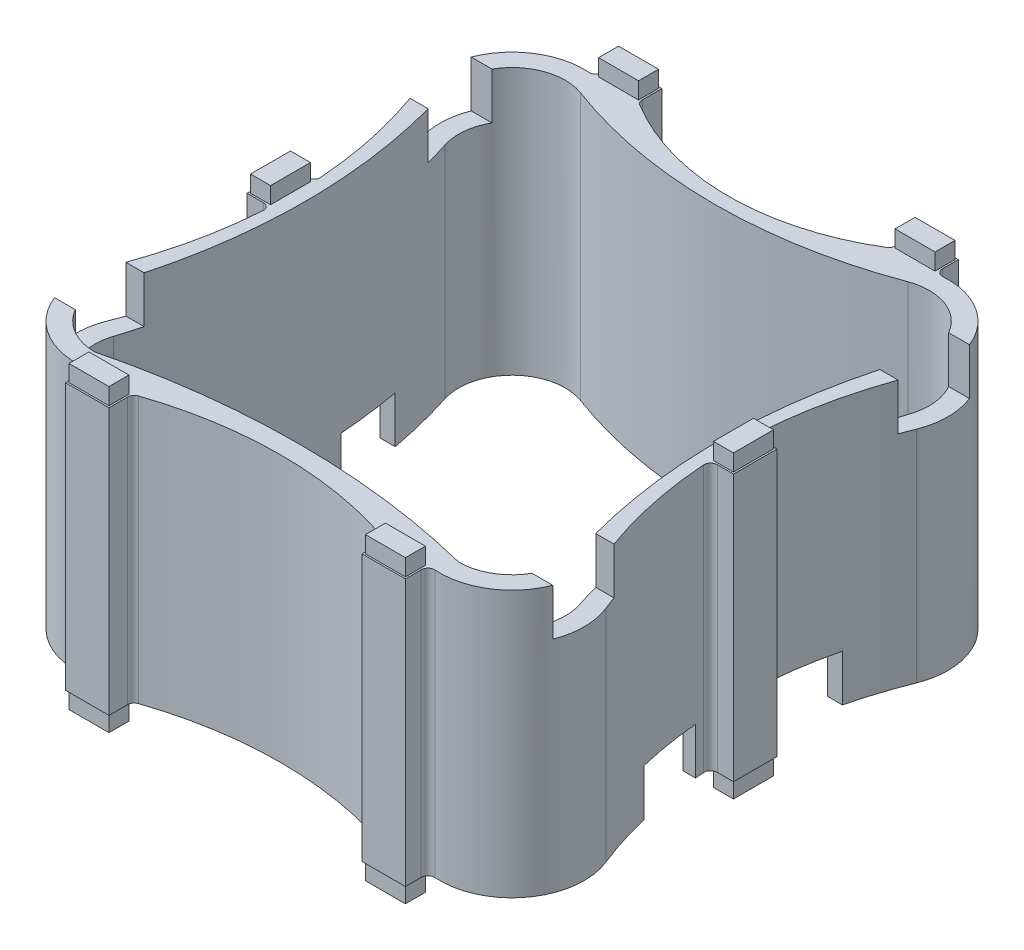
SolidWorks part; units mm, degrees
material "尼龙 101"
ref_plane "前视基准面" through (0, 0, 0) normal (0, 0, 1) x (1, 0, 0)
ref_plane "上视基准面" through (0, 0, 0) normal (0, 1, 0) x (1, 0, 0)
ref_plane "右视基准面" through (0, 0, 0) normal (1, 0, 0) x (0, 0, -1)
sketch "参考面" plane through (0, 0, 0) normal (0, 1, 0) x (1, 0, 0)
  line L9 (-126.3139, 0) -> (116.7252, 0) construction
  line L10 (121.4406, 121.4406) -> (-121.4406, -121.4406) construction
  line L19 (-81.1154, 0) -> (102.0168, 0) construction
  line L20 (-108.2303, 108.2303) -> (124.7404, -124.7404) construction
  line L37 (0, 0) -> (86.2111, -62.636) construction
  line L56 (0, 63.4476) -> (0, -83.7805) construction
  line L92 (67.1165, -56.1685) -> (56.6027, -48.5298)
  line L94 (74.1596, -46.4745) -> (63.6458, -38.8359)
  line L111 (14.4084, 23.7665) -> (0, 9.3581)
  line L112 (21.4, 67.209) -> (28.6, 67.209)
  line L121 (4.0949, -56.1675) -> (4.0949, -53.2193)
  line L122 (-3.5956, -56.6668) -> (3.5956, -56.6668)
  line L123 (3.5956, -40.6902) -> (-3.5938, -40.6902)
  line L124 (4.0949, -41.1895) -> (4.0949, -44.1377)
  line L125 (-4.0949, -56.1675) -> (-4.0949, -53.2179)
  line L126 (-4.0949, -44.1363) -> (-4.0949, -41.1876)
  line L127 (-4.5418, -52.8684) -> (-4.4444, -52.8684)
  line L128 (-8.5359, -48.8743) -> (-8.5359, -48.4799)
  line L129 (8.5359, -48.8757) -> (8.5359, -48.4813)
  line L130 (4.4444, -52.8698) -> (4.5418, -52.8698)
  line L131 (4.5418, -44.4872) -> (4.4444, -44.4872)
  line L132 (-4.5418, -44.4858) -> (-4.4444, -44.4858)
  line L180 (-67.1165, 56.1685) -> (-56.6027, 48.5298)
  line L181 (-74.1596, 46.4745) -> (-63.6458, 38.8359)
  line L182 (-74.1596, -46.4745) -> (-63.6458, -38.8359)
  line L183 (-67.1165, -56.1685) -> (-56.6027, -48.5298)
  line L194 (-18.9731, -62.4083) -> (18.9712, -62.4083) construction
  line L200 (-11.2634, 52.145) -> (-6.2707, 52.145) construction
  line L201 (-11.2634, 50.8469) -> (-6.2707, 50.8469)
  line L202 (-11.2634, 53.4431) -> (-6.2707, 53.4431)
  line L206 (5.7117, 52.145) -> (0.719, 52.145) construction
  line L207 (5.7117, 53.4431) -> (0.719, 53.4431)
  line L208 (5.7117, 50.8469) -> (0.719, 50.8469)
  line L209 (74.1596, 46.4745) -> (63.6458, 38.8359)
  line L210 (43.9796, 31.9531) -> (60.1362, 43.6915) construction
  line L211 (67.1165, 56.1685) -> (56.6027, 48.5298)
  line L213 (-23.7665, 14.4084) -> (-9.3581, 0)
  line L214 (-58.8004, 0) -> (57.5251, 0) construction
  line L215 (-23.7665, -14.4084) -> (-9.3581, 0)
  line L241 (20.9, 49.291) -> (20.9, 66.709)
  line L242 (21.4, 48.791) -> (28.6, 48.791)
  line L243 (-14.4084, 23.7665) -> (0, 9.3581)
  line L244 (20.9, 58) -> (35.2287, 58) construction
  line L245 (25, 67.209) -> (25, 48.791) construction
  line L246 (29.1, 66.709) -> (29.1, 49.291)
  line L247 (23.7665, -14.4084) -> (9.3581, 0)
  line L248 (23.7665, 14.4084) -> (9.3581, 0)
  line L249 (-14.4084, -23.7665) -> (0, -9.3581)
  line L250 (14.4084, -23.7665) -> (0, -9.3581)
  line L255 (25.5, -41.5) -> (19, -41.5)
  line L256 (-25.5, 41.5) -> (-19, 41.5)
  line L257 (-25.5, 41.5) -> (-25.5, 38)
  line L258 (-25.5, 38) -> (-19, 38)
  line L259 (-19, 41.5) -> (-19, 38)
  line L260 (-36.5, 3.25) -> (-33, 3.25)
  line L261 (-36.5, 3.25) -> (-36.5, -3.25)
  line L262 (-36.5, -3.25) -> (-33, -3.25)
  line L263 (-33, 3.25) -> (-33, -3.25)
  line L264 (-25.5, -38) -> (-19, -38)
  line L265 (-25.5, -38) -> (-25.5, -41.5)
  line L266 (-25.5, -41.5) -> (-19, -41.5)
  line L267 (-19, -38) -> (-19, -41.5)
  line L268 (19, -38) -> (19, -41.5)
  line L269 (25.5, -38) -> (19, -38)
  line L270 (25.5, -38) -> (25.5, -41.5)
  line L271 (36.5, -3.25) -> (33, -3.25)
  line L272 (33, 3.25) -> (33, -3.25)
  line L273 (36.5, 3.25) -> (33, 3.25)
  line L274 (36.5, 3.25) -> (36.5, -3.25)
  line L275 (25.5, 38) -> (19, 38)
  line L276 (19, 41.5) -> (19, 38)
  line L277 (25.5, 41.5) -> (25.5, 38)
  line L278 (25.5, 41.5) -> (19, 41.5)
  circle A40 centre (9.9853, 9.9853) radius 1.0734
  circle A65 centre (12.7313, 12.7313) radius 1.0734
  circle A66 centre (15.2276, 15.2276) radius 1.5477
  circle A67 centre (-15.2276, 15.2276) radius 1.5477
  circle A68 centre (-12.7313, 12.7313) radius 1.0734
  circle A69 centre (-9.9853, 9.9853) radius 1.0734
  circle A70 centre (-9.9853, -9.9853) radius 1.0734
  circle A71 centre (-12.7313, -12.7313) radius 1.0734
  circle A72 centre (-15.2276, -15.2276) radius 1.5477
  circle A82 centre (15.2276, -15.2276) radius 1.5477
  circle A83 centre (12.7313, -12.7313) radius 1.0734
  circle A84 centre (9.9853, -9.9853) radius 1.0734
  circle A85 centre (27.9589, -27.9589) radius 3.1454
  circle A86 centre (-27.9589, -27.9589) radius 3.1454
  circle A101 centre (-27.9589, 27.9589) radius 3.1454
  circle A102 centre (27.9589, 27.9589) radius 3.1454
  circle A104 centre (43.9796, -31.9531) radius 1.5477
  circle A105 centre (60.1362, -43.6915) radius 1.5477
  circle A106 centre (-60.1362, -43.6915) radius 1.5477
  circle A113 centre (-23.2458, 52.145) radius 1.2981
  circle A114 centre (-43.9796, -31.9531) radius 1.5477
  circle A115 centre (60.1362, 43.6915) radius 1.5477
  circle A116 centre (43.9796, 31.9531) radius 1.5477
  circle A117 centre (-43.9796, 31.9531) radius 1.5477
  circle A118 centre (-60.1362, 43.6915) radius 1.5477
  arc A120 (67.1165, -56.1685) -> (74.1596, -46.4745) centre (70.638, -51.3215) ccw
  arc A121 (27.2174, -63.5024) -> (56.6027, -48.5298) centre (45.7245, -63.5024) cw
  arc A128 (-4.0949, -56.1675) -> (-3.5956, -56.6668) centre (-4.0949, -56.6668) ccw
  arc A129 (4.0949, -56.1675) -> (3.5956, -56.6668) centre (4.0949, -56.6668) cw
  arc A130 (4.0949, -41.1895) -> (3.5956, -40.6902) centre (4.0949, -40.6902) ccw
  arc A131 (-4.0949, -41.1876) -> (-3.5938, -40.6902) centre (-4.0931, -40.6884) cw
  arc A132 (8.5359, -48.4813) -> (4.5418, -44.4872) centre (4.5418, -48.4813) ccw
  arc A133 (-4.5418, -44.4858) -> (-8.5359, -48.4799) centre (-4.5418, -48.4799) ccw
  arc A134 (-4.5418, -52.8684) -> (-8.5359, -48.8743) centre (-4.5418, -48.8743) cw
  arc A135 (8.5359, -48.8757) -> (4.5418, -52.8698) centre (4.5418, -48.8757) cw
  arc A136 (4.0949, -44.1377) -> (4.4444, -44.4872) centre (4.4444, -44.1377) ccw
  arc A137 (4.0949, -53.2193) -> (4.4444, -52.8698) centre (4.4444, -53.2193) cw
  arc A138 (-4.0949, -44.1363) -> (-4.4444, -44.4858) centre (-4.4444, -44.1363) cw
  arc A139 (-4.0949, -53.2179) -> (-4.4444, -52.8684) centre (-4.4444, -53.2179) ccw
  arc A165 (-11.2634, 50.8469) -> (-11.2634, 53.4431) centre (-11.2634, 52.145) cw
  arc A166 (-6.2707, 53.4431) -> (-6.2707, 50.8469) centre (-6.2707, 52.145) cw
  arc A169 (5.7117, 53.4431) -> (5.7117, 50.8469) centre (5.7117, 52.145) cw
  arc A170 (0.719, 50.8469) -> (0.719, 53.4431) centre (0.719, 52.145) cw
  circle A175 centre (0, -38.4435) radius 1.5477
  circle A176 centre (0, -58.9135) radius 1.5477
  arc A177 (67.1165, 56.1685) -> (74.1596, 46.4745) centre (70.638, 51.3215) cw
  arc A178 (63.6458, 38.8359) -> (63.6458, -38.8359) centre (91.8617, 0) ccw
  circle A179 centre (43.9796, -31.9531) radius 5.9912 construction
  arc A180 (35.3497, 58.9683) -> (56.6027, 48.5298) centre (48.7329, 59.3617) ccw
  arc A181 (-67.1165, 56.1685) -> (-74.1596, 46.4745) centre (-70.638, 51.3215) ccw
  arc A182 (-35.3497, 58.9683) -> (-56.6027, 48.5298) centre (-48.7329, 59.3617) cw
  arc A183 (-63.6458, 38.8359) -> (-63.6458, -38.8359) centre (-91.8617, 0) cw
  arc A184 (-67.1165, -56.1685) -> (-74.1596, -46.4745) centre (-70.638, -51.3215) cw
  arc A185 (-27.2174, -63.5024) -> (-56.6027, -48.5298) centre (-45.7245, -63.5024) ccw
  arc A190 (-23.7665, 14.4084) -> (-29.7764, 19.3723) centre (-52.8107, -14.6358) ccw
  arc A191 (-23.7665, -14.4084) -> (-29.7764, -19.3723) centre (-52.8107, 14.6358) cw
  arc A192 (-29.7764, -19.3723) -> (-29.7764, 19.3723) centre (-91.8617, 0) ccw
  circle A202 centre (25, 69.659) radius 1.05
  arc A203 (20.9, 66.709) -> (21.4, 67.209) centre (20.9, 67.209) cw
  arc A204 (20.9, 49.291) -> (21.4, 48.791) centre (20.9, 48.791) ccw
  circle A205 centre (25, 46.341) radius 1.05
  arc A206 (29.1, 66.709) -> (28.6, 67.209) centre (29.1, 67.209) ccw
  arc A207 (29.1, 49.291) -> (28.6, 48.791) centre (29.1, 48.791) cw
  arc A208 (-14.4084, 23.7665) -> (-19.3723, 29.7764) centre (14.6358, 52.8107) cw
  arc A209 (-19.3723, 29.7764) -> (19.3723, 29.7764) centre (0, 91.8617) ccw
  arc A210 (14.4084, 23.7665) -> (19.3723, 29.7764) centre (-14.6358, 52.8107) ccw
  arc A211 (23.7665, 14.4084) -> (29.7764, 19.3723) centre (52.8107, -14.6358) cw
  arc A212 (29.7764, 19.3723) -> (29.7764, -19.3723) centre (91.8617, 0) ccw
  arc A213 (23.7665, -14.4084) -> (29.7764, -19.3723) centre (52.8107, 14.6358) ccw
  arc A214 (14.4084, -23.7665) -> (19.3723, -29.7764) centre (-14.6358, -52.8107) cw
  arc A215 (19.3723, -29.7764) -> (-19.3723, -29.7764) centre (0, -91.8617) ccw
  arc A216 (-14.4084, -23.7665) -> (-19.3723, -29.7764) centre (14.6358, -52.8107) ccw
  point P77 (0, 0)
  point P112 (-8.7671, 52.145)
  point P168 (3.2153, 52.145)
  point P443 (0, 0)
  dimension "D1" = 4
  dimension "D3" = 58
  dimension "D5" = 8.2
  dimension "D2" = 0.5
  dimension "D4" = 2.45
  dimension "D6" = 7.2
  dimension "D7" = 25
  dimension "D8" = 19
  dimension "D9" = 33
  dimension "D14" = 6.5
  dimension "D15" = 3.5
  dimension "D16" = 38
  dimension "D17" = 38
sketch "草图2" plane through (0, 0, 0) normal (0, 1, 0) x (1, 0, 0)
  line L1 (-61.3007, 0) -> (77.257, 0) construction
  line L8 (-33, 3.25) -> (-36.5, 3.25)
  line L9 (-36.5, 3.25) -> (-36.5, -3.25)
  line L31 (-36.5, -3.25) -> (-33, -3.25)
  line L33 (-25.5, 38) -> (-25.5, 41.5)
  line L56 (-25.5, 41.5) -> (-19, 41.5)
  line L57 (-19, 41.5) -> (-19, 38)
  line L58 (-25.5, -38) -> (-25.5, -41.5)
  line L59 (-25.5, -41.5) -> (-19, -41.5)
  line L60 (-19, -41.5) -> (-19, -38)
  line L61 (19, -41.5) -> (19, -38)
  line L62 (25.5, -41.5) -> (19, -41.5)
  line L63 (25.5, -38) -> (25.5, -41.5)
  line L64 (19, 41.5) -> (19, 38)
  line L65 (25.5, 41.5) -> (19, 41.5)
  line L66 (25.5, 38) -> (25.5, 41.5)
  line L67 (36.5, -3.25) -> (33, -3.25)
  line L68 (36.5, 3.25) -> (36.5, -3.25)
  line L69 (33, 3.25) -> (36.5, 3.25)
  line L74 (-126.3139, 0) -> (116.7252, 0) construction
  line L75 (0, 68.5797) -> (0, -68.5797) construction
  line L76 (0, 63.4476) -> (0, -83.7805) construction
  line L77 (-108.2303, 108.2303) -> (124.7404, -124.7404) construction
  arc A49 (-25.5, 38) -> (-37.3844, 23.3059) centre (-27.3145, 27.3145) ccw
  arc A52 (-24.5842, 34.8413) -> (-34.9442, 24.8864) centre (-27.3145, 27.3145) ccw
  arc A53 (-34.9442, -24.8864) -> (-34.9442, 24.8864) centre (-113.1442, 0) ccw
  arc A55 (-37.3844, -23.3059) -> (-33, -3.25) centre (-95.9302, 0) ccw
  arc A56 (-25.5, -38) -> (-37.3844, -23.3059) centre (-27.3145, -27.3145) cw
  arc A57 (-27.3357, -35.3212) -> (-34.9442, -24.8864) centre (-27.3145, -27.3145) cw
  arc A59 (-33, 3.25) -> (-37.3844, 23.3059) centre (-95.9302, 0) ccw
  arc A62 (33, 3.25) -> (37.3844, 23.3059) centre (95.9302, 0) cw
  arc A65 (27.3357, -35.3212) -> (34.9442, -24.8864) centre (27.3145, -27.3145) ccw
  arc A66 (25.5, -38) -> (37.3844, -23.3059) centre (27.3145, -27.3145) ccw
  arc A69 (37.3844, -23.3059) -> (33, -3.25) centre (95.9302, 0) cw
  arc A70 (34.9442, -24.8864) -> (34.9442, 24.8864) centre (113.1442, 0) cw
  arc A71 (24.5842, 34.8413) -> (34.9442, 24.8864) centre (27.3145, 27.3145) cw
  arc A72 (25.5, 38) -> (37.3844, 23.3059) centre (27.3145, 27.3145) cw
  arc A73 (-19, 38) -> (19, 38) centre (0, 67.9818) ccw
  arc A74 (-24.5842, 34.8413) -> (24.5842, 34.8413) centre (0, 100.6181) ccw
  arc A75 (-19, -38) -> (19, -38) centre (0, -91.6977) cw
  arc A76 (-27.3357, -35.3212) -> (27.3357, -35.3212) centre (0, -143.9681) cw
extrude "凸台-拉伸1" add sketch "草图2" against normal blind 40
sketch "草图5" plane through (0, 0, 0) normal (0, 1, 0) x (1, 0, 0)
  line L0 (-68.648, 0) -> (77.219, 0) construction
  line L1 (-126.3139, 0) -> (116.7252, 0) construction
  line L2 (0, 57.3258) -> (0, -69.9488) construction
  line L3 (0, 63.4476) -> (0, -83.7805) construction
  line L4 (-36.5, 3.25) -> (-33, 3.25) construction
  line L5 (-36.25, 3) -> (-33.25, 3)
  line L6 (-36.25, 3) -> (-36.25, -3)
  line L7 (-36.25, -3) -> (-33.25, -3)
  line L8 (-33.25, 3) -> (-33.25, -3)
  line L9 (-36.5, 3.25) -> (-36.5, -3.25) construction
  line L10 (-19, -38) -> (-19, -41.5) construction
  line L11 (-25.25, -38.25) -> (-19.25, -38.25)
  line L12 (-25.25, -38.25) -> (-25.25, -41.25)
  line L13 (-25.25, -41.25) -> (-19.25, -41.25)
  line L14 (-19.25, -38.25) -> (-19.25, -41.25)
  line L15 (-25.5, -41.5) -> (-19, -41.5) construction
  line L16 (-25.25, 41.25) -> (-19.25, 41.25)
  line L17 (-19.25, 38.25) -> (-19.25, 41.25)
  line L18 (-25.25, 38.25) -> (-19.25, 38.25)
  line L19 (-25.25, 38.25) -> (-25.25, 41.25)
  line L20 (25.25, 38.25) -> (25.25, 41.25)
  line L21 (25.25, 38.25) -> (19.25, 38.25)
  line L22 (19.25, 38.25) -> (19.25, 41.25)
  line L23 (25.25, 41.25) -> (19.25, 41.25)
  line L24 (19.25, -38.25) -> (19.25, -41.25)
  line L25 (25.25, -41.25) -> (19.25, -41.25)
  line L26 (25.25, -38.25) -> (25.25, -41.25)
  line L27 (25.25, -38.25) -> (19.25, -38.25)
  line L28 (33.25, 3) -> (33.25, -3)
  line L29 (36.25, -3) -> (33.25, -3)
  line L30 (36.25, 3) -> (36.25, -3)
  line L31 (36.25, 3) -> (33.25, 3)
  dimension "D1" = 0.25
  dimension "D2" = 0.25
  dimension "D3" = 3
  dimension "D4" = 0.25
  dimension "D5" = 0.25
extrude "凸台-拉伸3" add sketch "草图5" along normal blind 2.5
sketch "草图6" plane through (0, -40, 0) normal (0, -1, 0) x (1, 0, 0)
  line L0 (-44.389, 0) -> (42.3877, 0) construction
  line L1 (0, 51.2716) -> (0, -51.2716) construction
  line L2 (-25.25, 41.25) -> (-19.25, 41.25)
  line L3 (-36.25, 3) -> (-33.25, 3)
  line L4 (-36.25, 3) -> (-36.25, -3)
  line L5 (-36.25, -3) -> (-33.25, -3)
  line L6 (-33.25, 3) -> (-33.25, -3)
  line L7 (-25.25, -38.25) -> (-19.25, -38.25)
  line L8 (-25.25, -38.25) -> (-25.25, -41.25)
  line L9 (-25.25, -41.25) -> (-19.25, -41.25)
  line L10 (-19.25, -38.25) -> (-19.25, -41.25)
  line L11 (-19.25, 38.25) -> (-19.25, 41.25)
  line L12 (-25.25, 38.25) -> (-19.25, 38.25)
  line L13 (-25.25, 38.25) -> (-25.25, 41.25)
  line L14 (25.25, 38.25) -> (25.25, 41.25)
  line L15 (25.25, 38.25) -> (19.25, 38.25)
  line L16 (19.25, 38.25) -> (19.25, 41.25)
  line L17 (19.25, -38.25) -> (19.25, -41.25)
  line L18 (25.25, -41.25) -> (19.25, -41.25)
  line L19 (25.25, -38.25) -> (25.25, -41.25)
  line L20 (25.25, -38.25) -> (19.25, -38.25)
  line L21 (33.25, 3) -> (33.25, -3)
  line L22 (36.25, -3) -> (33.25, -3)
  line L23 (36.25, 3) -> (36.25, -3)
  line L24 (36.25, 3) -> (33.25, 3)
  line L25 (25.25, 41.25) -> (19.25, 41.25)
  line L26 (-36.5, 3.25) -> (-33, 3.25) construction
  line L27 (-36.5, -3.25) -> (-36.5, 3.25) construction
  line L28 (-25.5, -41.5) -> (-25.5, -38) construction
  line L29 (-19, -41.5) -> (-25.5, -41.5) construction
  dimension "D1" = 0.25
  dimension "D2" = 0.25
  dimension "D3" = 0.25
  dimension "D4" = 0.25
  dimension "D5" = 3
extrude "凸台-拉伸4" add sketch "草图6" along normal blind 2.5
fillet "圆角1" radius 1 12 edges at (33, -20, -3.25) (25.5, -20, -38) (-19, -20, -38) (19, -20, -38) (-25.5, -20, -38) (-33, -20, -3.25) (19, -20, 38) (33, -20, 3.25) (25.5, -20, 38) (-19, -20, 38) (-25.5, -20, 38) (-33, -20, 3.25)
sketch "草图7" plane through (0, 0, 0) normal (0, 1, 0) x (1, 0, 0)
  line L0 (-43.0337, 0) -> (42.851, 0) construction
  line L1 (0, 36.718) -> (0, -44.8375) construction
  line L2 (0, 0) -> (-41.2356, -29.9594) construction
  line L3 (-36.6337, -21.3237) -> (-33.8986, -21.3237)
  line L4 (-37.4219, -31.2746) -> (-34.2733, -31.2746)
  line L5 (36.6337, -21.3237) -> (33.8986, -21.3237)
  line L6 (37.4219, -31.2746) -> (34.2733, -31.2746)
  line L8 (-36.6337, 21.3237) -> (-33.8986, 21.3237)
  line L9 (-37.4219, 31.2746) -> (-34.2733, 31.2746)
  line L10 (37.4219, 31.2746) -> (34.2733, 31.2746)
  line L11 (36.6337, 21.3237) -> (33.8986, 21.3237)
  arc A0 (-34.9442, -24.8864) -> (-34.2733, -31.2746) centre (-27.2797, -27.3109) ccw
  arc A1 (-37.606, -23.8549) -> (-37.4219, -31.2746) centre (-27.2797, -27.3109) ccw
  arc A2 (-37.606, -23.8549) -> (-36.6337, -21.3237) centre (-95.9302, 0) ccw
  arc A3 (-34.9442, -24.8864) -> (-33.8986, -21.3237) centre (-113.1442, 0) ccw
  arc A4 (34.9442, -24.8864) -> (33.8986, -21.3237) centre (113.1442, 0) cw
  arc A5 (37.606, -23.8549) -> (36.6337, -21.3237) centre (95.9302, 0) cw
  arc A6 (37.606, -23.8549) -> (37.4219, -31.2746) centre (27.2797, -27.3109) cw
  arc A7 (34.9442, -24.8864) -> (34.2733, -31.2746) centre (27.2797, -27.3109) cw
  arc A12 (-34.9442, 24.8864) -> (-33.8986, 21.3237) centre (-113.1442, 0) cw
  arc A13 (-37.606, 23.8549) -> (-36.6337, 21.3237) centre (-95.9302, 0) cw
  arc A14 (-37.606, 23.8549) -> (-37.4219, 31.2746) centre (-27.2797, 27.3109) cw
  arc A15 (-34.9442, -24.8864) -> (-34.9442, 24.8864) centre (-113.1442, 0) ccw construction
  arc A16 (-34.9442, 24.8864) -> (-34.2733, 31.2746) centre (-27.2797, 27.3109) cw
  arc A17 (34.9442, 24.8864) -> (34.2733, 31.2746) centre (27.2797, 27.3109) ccw
  arc A18 (37.606, 23.8549) -> (37.4219, 31.2746) centre (27.2797, 27.3109) ccw
  arc A19 (37.606, 23.8549) -> (36.6337, 21.3237) centre (95.9302, 0) ccw
  arc A20 (34.9442, 24.8864) -> (33.8986, 21.3237) centre (113.1442, 0) ccw
  arc A22 (-34.9442, -24.8864) -> (-27.3357, -35.3212) centre (-27.3145, -27.3145) ccw construction
  point P2 (0, 0)
  point P29 (0, 0)
  point P31 (0, 0)
  point P32 (0, 0)
  point P41 (-33.7562, -20.7875)
  point P49 (-34.5298, -30.7862)
  point P50 (0, 0)
  point P51 (-34.5631, -30.716)
  point P55 (-35.156, -25.5423)
  point P56 (-35.1054, -25.3873)
  point P57 (-34.7615, -24.3047)
  point P58 (-35.0889, -25.3986)
  point P59 (-35.3177, -27.5624)
  point P60 (-35.3135, -27.6724)
  point P61 (-34.9638, 24.9479)
  point P62 (0, 0)
  point P63 (0, 0)
  point P64 (-34.2678, -31.285)
  point P65 (-34.3053, -31.2185)
  dimension "D1" = 36
extrude "电调过线" cut sketch "草图7" against normal blind 7
sketch "草图8" plane through (0, -40, 0) normal (0, -1, 0) x (1, 0, 0)
  line L0 (-48.2566, 0) -> (46.2095, 0) construction
  line L1 (0, 0) -> (0, -36.4146) construction
  line L2 (-33.1672, -5.62) -> (-31.2724, -5.62)
  line L3 (-34.7046, -14.9062) -> (-32.4449, -14.9062)
  line L4 (-34.7046, 14.9062) -> (-32.4449, 14.9062)
  line L5 (-33.1672, 5.62) -> (-31.2724, 5.62)
  line L6 (33.1672, -5.62) -> (31.2724, -5.62)
  line L7 (34.7046, -14.9062) -> (32.4449, -14.9062)
  line L8 (33.1672, 5.62) -> (31.2724, 5.62)
  line L9 (34.7046, 14.9062) -> (32.4449, 14.9062)
  arc A0 (-37.3844, -23.3059) -> (-33.0643, -4.3185) centre (-95.9302, 0) ccw construction
  arc A1 (-34.9442, -24.8864) -> (-34.9442, 24.8864) centre (-113.1442, 0) ccw construction
  arc A2 (-33.1672, -5.62) -> (-34.7046, -14.9062) centre (-95.9302, 0) cw
  arc A3 (-31.2724, -5.62) -> (-32.4449, -14.9062) centre (-113.1442, 0) cw
  arc A4 (-33.1672, 5.62) -> (-34.7046, 14.9062) centre (-95.9302, 0) ccw
  arc A5 (-31.2724, 5.62) -> (-32.4449, 14.9062) centre (-113.1442, 0) ccw
  arc A6 (33.1672, -5.62) -> (34.7046, -14.9062) centre (95.9302, 0) ccw
  arc A7 (31.2724, -5.62) -> (32.4449, -14.9062) centre (113.1442, 0) ccw
  arc A8 (31.2724, 5.62) -> (32.4449, 14.9062) centre (113.1442, 0) cw
  arc A9 (33.1672, 5.62) -> (34.7046, 14.9062) centre (95.9302, 0) cw
extrude "电源过线" cut sketch "草图8" against normal blind 7
